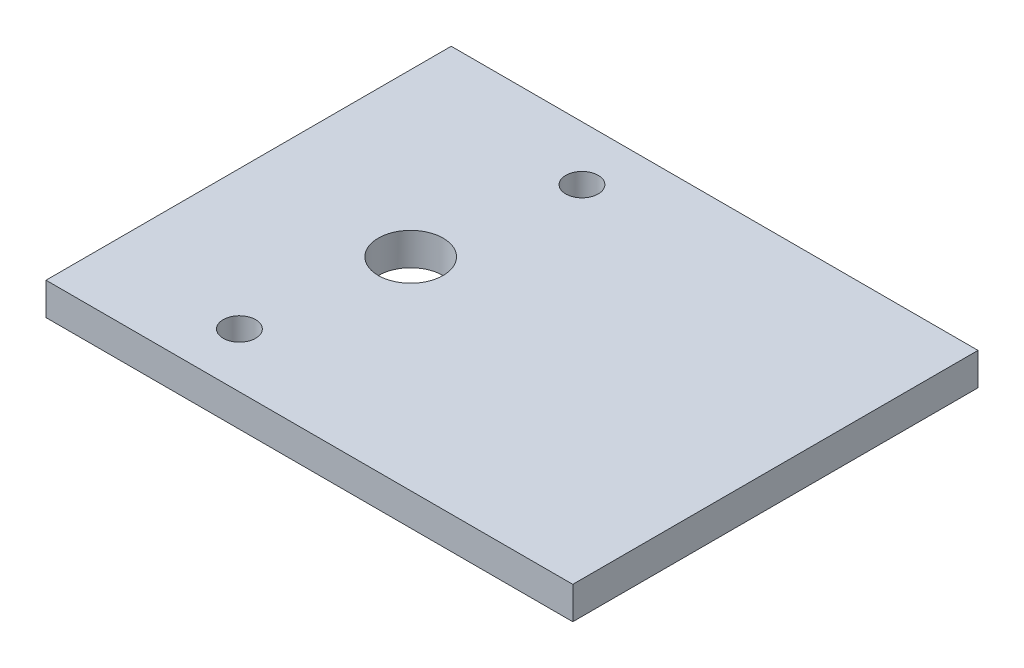
SolidWorks part; units mm, degrees
material "1060 Alloy"
ref_plane "Front Plane" through (0, 0, 0) normal (0, 0, 1) x (1, 0, 0)
ref_plane "Top Plane" through (0, 0, 0) normal (0, 1, 0) x (1, 0, 0)
ref_plane "Right Plane" through (0, 0, 0) normal (1, 0, 0) x (0, 0, -1)
sketch "Sketch2" plane through (0, 0, 0) normal (0, 0, 1) x (1, 0, 0)
  line L3 (4, 4) -> (90, 4)
  line L4 (90, 4) -> (90, 0)
  line L5 (90, 0) -> (0, 0)
  line L6 (0, 0) -> (0, 4)
  line L7 (0, 4) -> (4, 4)
  dimension "D2" = 90
  dimension "D3" = 4
extrude "Boss-Extrude1" add sketch "Sketch2" along normal blind 50
sketch "Sketch3" plane through (0, 4, 0) normal (0, 1, 0) x (1, 0, 0)
  line L0 (90, 0) -> (0, 0) construction
  line L2 (90, -50) -> (90, 0) construction
  circle A0 centre (20, -25) radius 4
  dimension "D1" = 8
  dimension "D2" = 25
  dimension "D3" = 70
extrude "Cut-Extrude1" cut sketch "Sketch3" against normal blind 10
sketch "Sketch4" plane through (0, 4, 0) normal (0, 1, 0) x (1, 0, 0)
  line L0 (65, 0) -> (65, -50)
  line L1 (90, 0) -> (0, 0) construction
  line L2 (90, -50) -> (0, -50) construction
  line L3 (65, -50) -> (90, -50)
  line L4 (90, -50) -> (90, 0)
  line L5 (90, 0) -> (65, 0)
  dimension "D1" = 25
extrude "Cut-Extrude2" cut sketch "Sketch4" against normal blind 10
sketch "Sketch6" plane through (0, 4, 0) normal (0, 1, 0) x (1, 0, 0)
  circle A0 centre (17.1437, -43.2782) radius 2
  circle A1 centre (22.8563, -6.7218) radius 2
extrude "Cut-Extrude4" cut sketch "Sketch6" against normal through all
